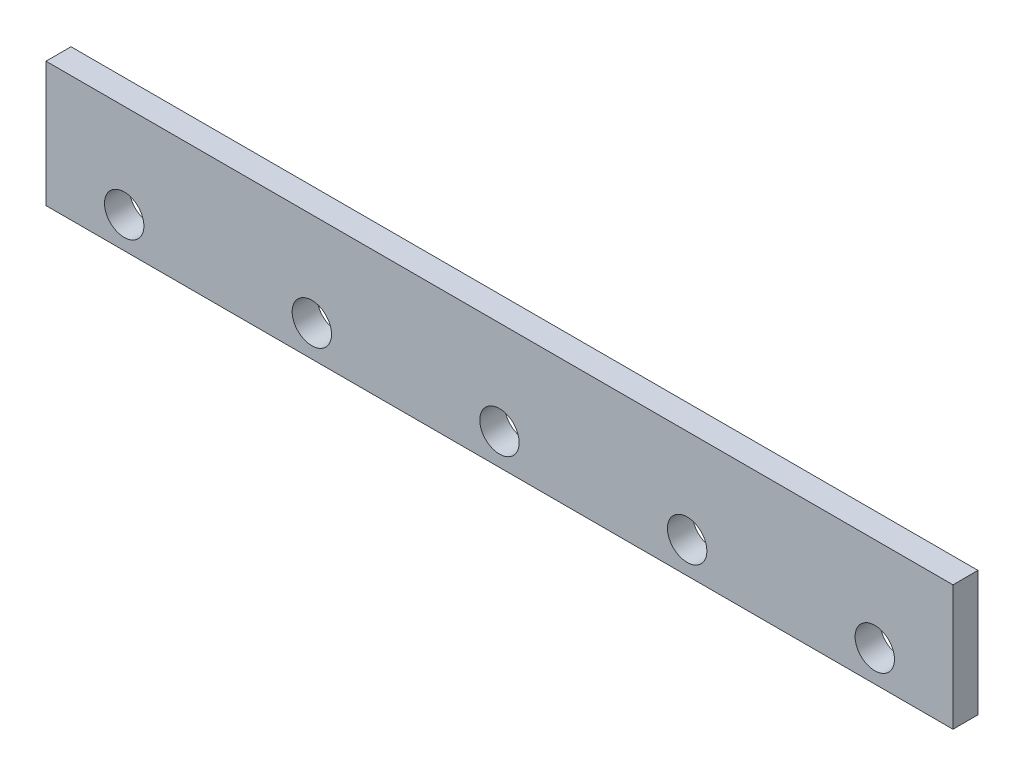
SolidWorks part; units mm, degrees
ref_plane "Alzado" through (0, 0, 0) normal (0, 0, 1) x (1, 0, 0)
ref_plane "Planta" through (0, 0, 0) normal (0, 1, 0) x (1, 0, 0)
ref_plane "Vista lateral" through (0, 0, 0) normal (1, 0, 0) x (0, 0, -1)
sketch "Croquis1" plane through (0, 0, 0) normal (0, 0, 1) x (1, 0, 0)
  line L0 (0, 20) -> (580, 20) construction
  line L1 (0, 0) -> (580, 0)
  line L2 (0, 0) -> (0, 80)
  line L3 (0, 80) -> (580, 80)
  line L4 (580, 0) -> (580, 80)
  circle A0 centre (50, 20) radius 12.6
  circle A1 centre (170, 20) radius 12.6
  circle A2 centre (290, 20) radius 12.6
  circle A3 centre (410, 20) radius 12.6
  circle A4 centre (530, 20) radius 12.6
  dimension "D4" = 25.2
  dimension "D6" = 120
  dimension "D7" = 120
  dimension "D8" = 120
  dimension "D9" = 120
  dimension "D1" = 580
  dimension "D2" = 80
  dimension "D3" = 20
  dimension "D5" = 50
extrude "Saliente-Extruir1" add sketch "Croquis1" along normal blind 16
